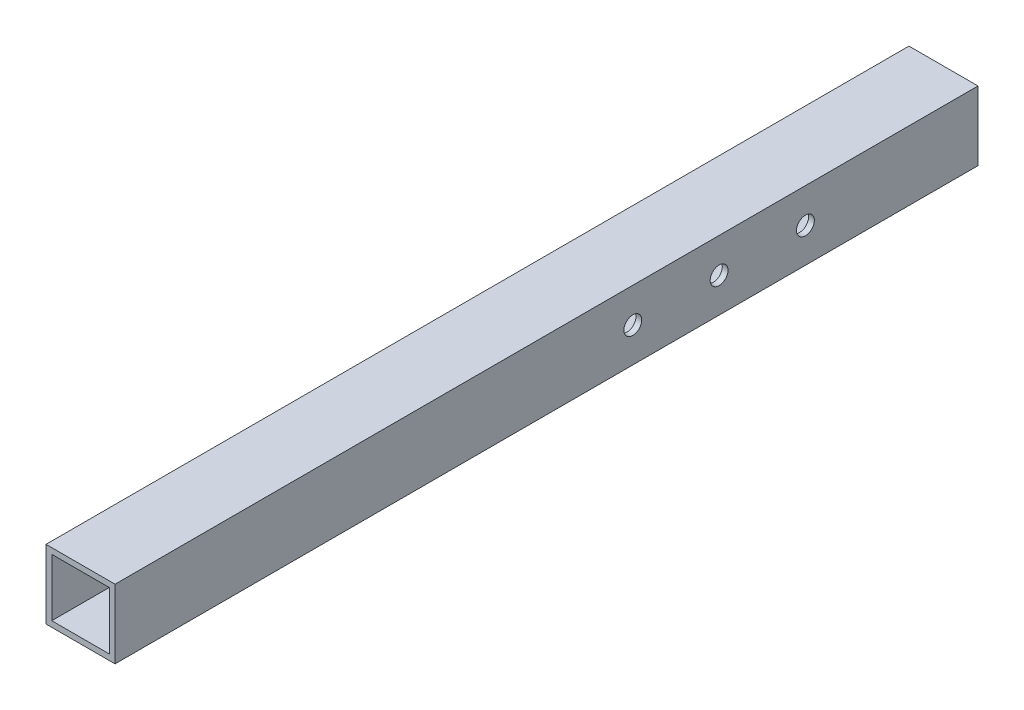
SolidWorks part; units mm, degrees
material "Thornel Mat VMA"
ref_plane "前视基准面" through (0, 0, 0) normal (0, 0, 1) x (1, 0, 0)
ref_plane "上视基准面" through (0, 0, 0) normal (0, 1, 0) x (1, 0, 0)
ref_plane "右视基准面" through (0, 0, 0) normal (1, 0, 0) x (0, 0, -1)
other "Configuration Table"
sketch "草图1" plane through (0, 0, 0) normal (0, 0, 1) x (1, 0, 0)
  line L0 (1, 1) -> (1, 11)
  line L1 (0, 0) -> (12, 0)
  line L2 (0, 0) -> (0, 12)
  line L3 (0, 12) -> (12, 12)
  line L4 (12, 0) -> (12, 12)
  line L5 (1, 11) -> (11, 11)
  line L6 (11, 1) -> (11, 11)
  line L7 (1, 1) -> (11, 1)
  dimension "D1" = 12
  dimension "D2" = 12
  dimension "D3" = 1
extrude "凸台-拉伸1" add sketch "草图1" along normal blind 150
sketch "草图3" plane through (12, 0, 0) normal (1, 0, 0) x (0, 1, 0)
  line L0 (6, 0) -> (6, 150) construction
  line L1 (0, 0) -> (12, 0) construction
  line L2 (0, 150) -> (12, 150) construction
  circle A0 centre (6, 30) radius 1.55
  circle A1 centre (6, 45) radius 1.55
  circle A2 centre (6, 60) radius 1.55
  dimension "D4" = 3.1
  dimension "D5" = 3.1
  dimension "D6" = 3.1
  dimension "D1" = 30
  dimension "D2" = 15
  dimension "D3" = 15
extrude "切除-拉伸1" cut sketch "草图3" against normal through all
